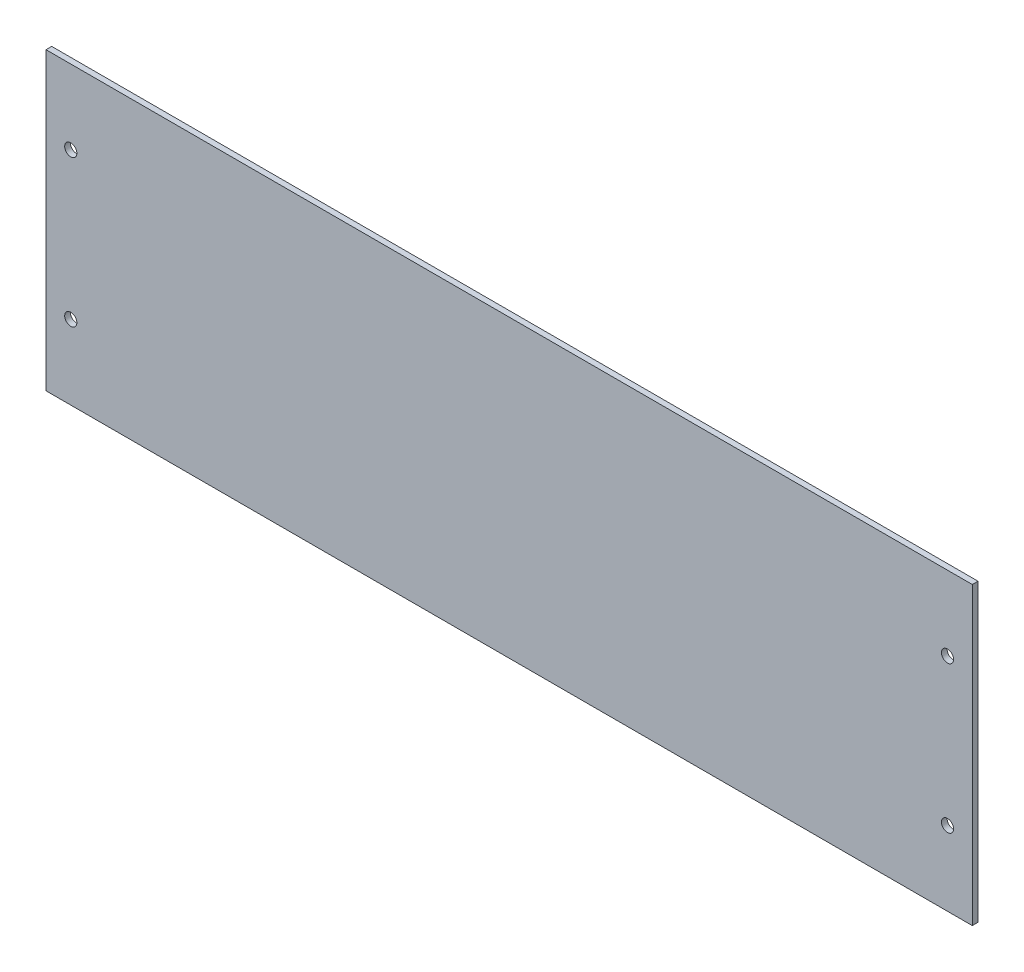
SolidWorks part; units mm, degrees
ref_plane "Front Plane" through (0, 0, 0) normal (0, 0, 1) x (1, 0, 0)
ref_plane "Top Plane" through (0, 0, 0) normal (0, 1, 0) x (1, 0, 0)
ref_plane "Right Plane" through (0, 0, 0) normal (1, 0, 0) x (0, 0, -1)
sketch "Sketch1" plane through (0, 0, 0) normal (0, 0, 1) x (1, 0, 0)
  line L0 (-61.5307, 80.4891) -> (-61.5307, -7.1083) construction
  line L1 (-68.0307, 76.2744) -> (174.9693, 76.2744)
  line L2 (-68.0307, 76.2744) -> (-68.0307, -1.2256)
  line L3 (-68.0307, -1.2256) -> (174.9693, -1.2256)
  line L4 (174.9693, 76.2744) -> (174.9693, -1.2256)
  line L5 (-77.9868, 56.7744) -> (-50.4869, 56.7744) construction
  line L6 (-76.1088, 18.2744) -> (-46.9525, 18.2744) construction
  line L7 (53.4693, 76.2744) -> (53.4693, -1.2256) construction
  circle A0 centre (-61.5307, 56.7744) radius 1.6
  circle A1 centre (-61.5307, 18.2744) radius 1.6
  circle A2 centre (168.4693, 18.2744) radius 1.6
  circle A3 centre (168.4693, 56.7744) radius 1.6
  dimension "D1" = 77.5
  dimension "D2" = 243
  dimension "D3" = 6.5
  dimension "D4" = 19.5
  dimension "D5" = 19.5
extrude "Boss-Extrude1" add sketch "Sketch1" along normal blind 1.5
